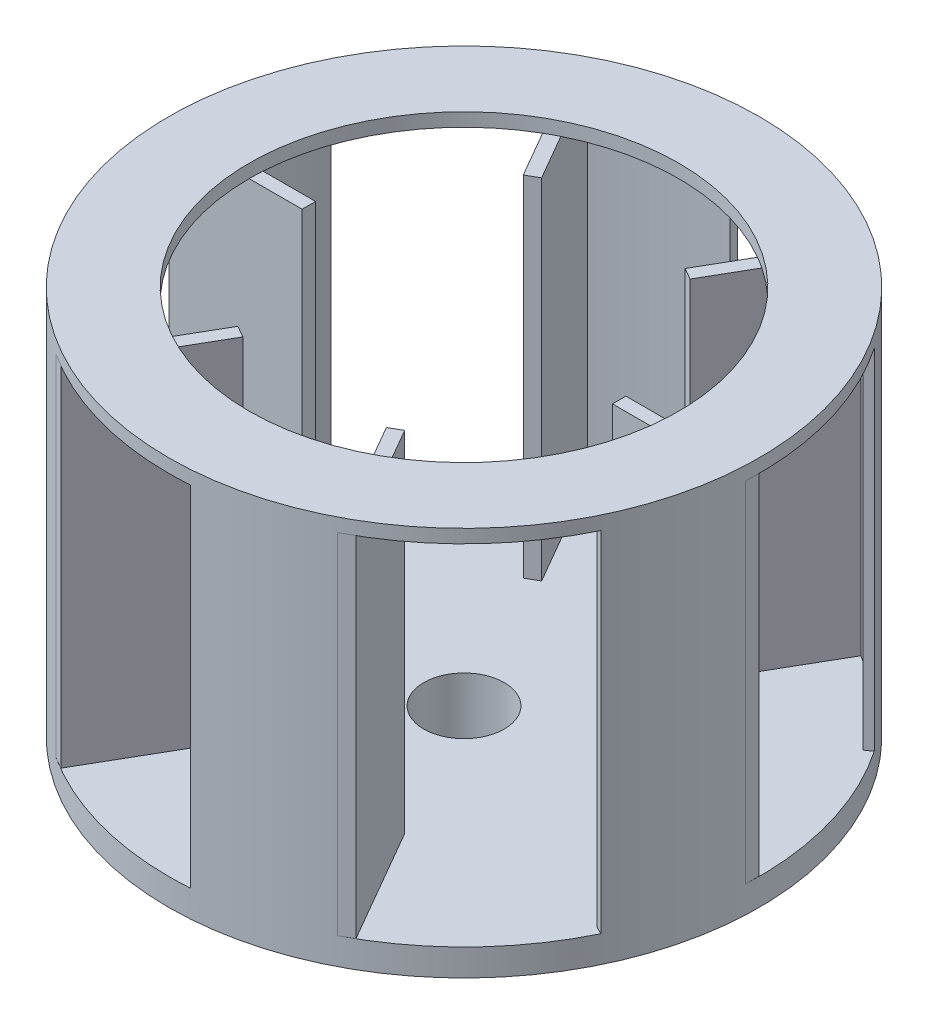
SolidWorks part; units mm, degrees
material "6061 Alloy"
ref_plane "Front Plane" through (0, 0, 0) normal (0, 0, 1) x (1, 0, 0)
ref_plane "Top Plane" through (0, 0, 0) normal (0, 1, 0) x (1, 0, 0)
ref_plane "Right Plane" through (0, 0, 0) normal (1, 0, 0) x (0, 0, -1)
sketch "Sketch1" plane through (0, 0, 0) normal (0, 1, 0) x (1, 0, 0)
  circle A0 centre (0, 0) radius 139.7
  dimension "D1" = 279.4
extrude "Boss-Extrude1" add sketch "Sketch1" against normal blind 6.35 from offset 92.075
sketch "Sketch2" plane through (0, 0, 0) normal (0, 1, 0) x (1, 0, 0)
  circle A0 centre (0, 0) radius 139.7
  dimension "D1" = 279.4
extrude "Boss-Extrude2" add sketch "Sketch2" along normal blind 12.7 from offset 92.075 separate body offset against normal yes
sketch "Sketch3" plane through (0, -79.375, 0) normal (0, 1, 0) x (1, 0, 0)
  line L0 (-139.7, 0) -> (139.7, 0) construction
  line L6 (0, 0) -> (125.6979, -60.96) construction
  line L12 (122.2698, -59.2975) -> (125.6979, -60.96)
  line L13 (76.5636, 0) -> (139.5556, 0)
  line L14 (76.5636, 0) -> (76.5636, -6.35)
  line L15 (76.5636, -6.35) -> (135.7416, -6.35)
  line L16 (139.5556, 0) -> (139.5556, -6.35)
  circle A3 centre (0, 0) radius 139.7 construction
  arc A6 (125.6979, -60.96) -> (139.5556, -6.35) centre (0, 0) ccw
  circle A7 centre (0, 0) radius 135.89
  arc A8 (122.2698, -59.2975) -> (135.7416, -6.35) centre (0, 0) ccw
  circle A9 centre (0, 0) radius 139.7 construction
  circle A10 centre (0, 0) radius 135.89 construction
  point P1 (0, 0)
  point P3 (133.5958, 40.8443)
  point P5 (0, 0)
  point P13 (135.89, 0)
  point P14 (0, 0)
  point P19 (129.9523, 39.7304)
  point P27 (139.7, 0)
  dimension "D6" = 60.96
  dimension "D7" = 62.992
  dimension "D1" = 6.35
  dimension "D3" = 3.81
  dimension "D4" = 279.4
extrude "Boss-Extrude3" add sketch "Sketch3" along normal up to surface (165.1 mm away) up to face at (0, 85.725, 139.7)
pattern_circular "CirPattern1" count 6 over 360 about axis through (0, 0, 0) along (0, 1, 0) of "Boss-Extrude3"
sketch "Sketch8" plane through (0, -92.075, 0) normal (0, -1, 0) x (1, 0, 0)
  circle A0 centre (0, 0) radius 38.1
  dimension "D1" = 76.2
extrude "Boss-Extrude4" add sketch "Sketch8" along normal blind 63.5
sketch "Sketch9" plane through (0, -155.575, 0) normal (0, -1, 0) x (1, 0, 0)
  circle A0 centre (0, 0) radius 19.05
  dimension "D1" = 38.1
extrude "Cut-Extrude1" cut sketch "Sketch9" against normal up to surface (76.2 mm away) up to face at (0, -79.375, 0)
sketch "Sketch10" plane through (0, 92.075, 0) normal (0, 1, 0) x (1, 0, 0)
  circle A0 centre (0, 0) radius 101.6
  dimension "D1" = 203.2
extrude "Cut-Extrude2" cut sketch "Sketch10" against normal up to surface (6.35 mm away) up to face at (0, 85.725, 0)
